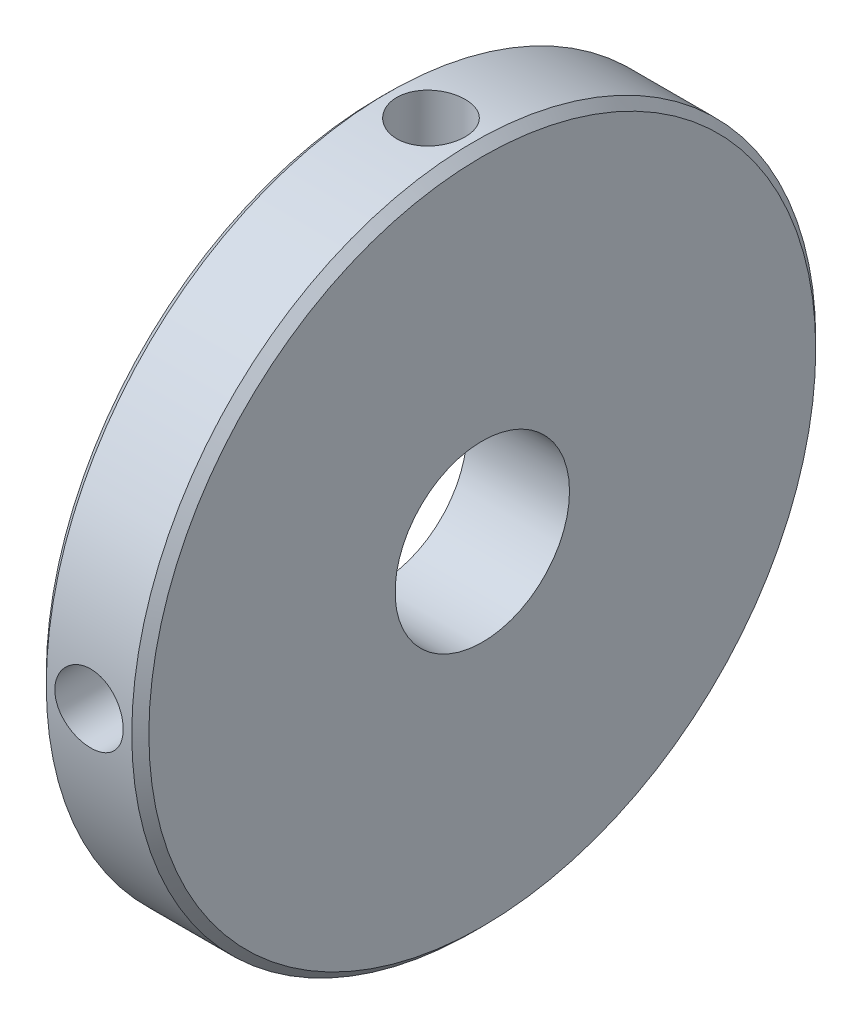
SolidWorks part; units mm, degrees
ref_plane "Face" through (0, 0, 0) normal (0, 0, 1) x (1, 0, 0)
ref_plane "Dessus" through (0, 0, 0) normal (0, 1, 0) x (1, 0, 0)
ref_plane "Droite" through (0, 0, 0) normal (1, 0, 0) x (0, 0, -1)
sketch "Esquisse1" plane through (0, 0, 0) normal (0, 0, 1) x (1, 0, 0)
  line L0 (-6.2215, 0) -> (35.632, 0) construction
  line L1 (0, 0) -> (6, 0)
  line L2 (0, 0) -> (0, 20)
  line L3 (0, 20) -> (6, 20)
  line L4 (6, 0) -> (6, 20)
  dimension "D1" = 20
  dimension "D2" = 6
revolve "Base-Révolution" add sketch "Esquisse1" angle 360 about L0
chamfer "Chanfrein1" distance 0.5 angle 45 2 edges at (6, 0, 20) (0, 0, 20)
sketch "Esquisse2" plane through (0, 0, 0) normal (0, 0, 1) x (1, 0, 0)
  line L0 (5.5, 20) -> (0.5, 20) construction
  line L1 (5, 20) -> (3, 20)
  line L2 (5, 20) -> (5, 15)
  line L3 (5, 15) -> (3, 13.7983)
  line L4 (3, 13.7983) -> (3, 20)
  line L5 (3, 20) -> (3, 12.9338) construction
  dimension "D1" = 2
  dimension "D2" = 59
  dimension "D3" = 5
  dimension "D4" = 3
revolve "Trou radial" cut sketch "Esquisse2" angle 360 about L5
ref_axis "Axe de révolution" through (43.7785, 0, 0) along (-1, 0, 0)
pattern_circular "Répétition circulaire1" count 4 over 360 about axis through (43.7785, 0, 0) along (-1, 0, 0) of "Trou radial"
hole_wizard "Trou taraudé M12x1.752" positions "Esquisse6" profile "Esquisse5" tap size "M12x1.75" standard "ISO" end condition through all
sketch "Esquisse6" plane through (6, 0, 0) normal (1, 0, 0) x (0, 0, -1)
  circle A0 centre (0, 0) radius 19.5 construction
  point P0 (0, 0)
sketch "Esquisse5" plane through (6, 0, 0) normal (0, 1, 0) x (0, 0, -1)
  line L0 (0, 0) -> (0, 6)
  line L1 (0, 6) -> (5.1, 6)
  line L2 (5.1, 6) -> (5.1, 0)
  line L5 (5.1, 0) -> (0, 0)
  line L11 (0, -6.35) -> (0, 107.95) construction
  dimension "Diamètre du perçage jusqu'au prochain" = 10.2
  dimension "Profondeur du perçage jusqu'au prochain" = 6
cosmetic thread "Représentation de filetage2"
equation "\"D4@Esquisse2\" = \"D2@Esquisse1\"/2"
